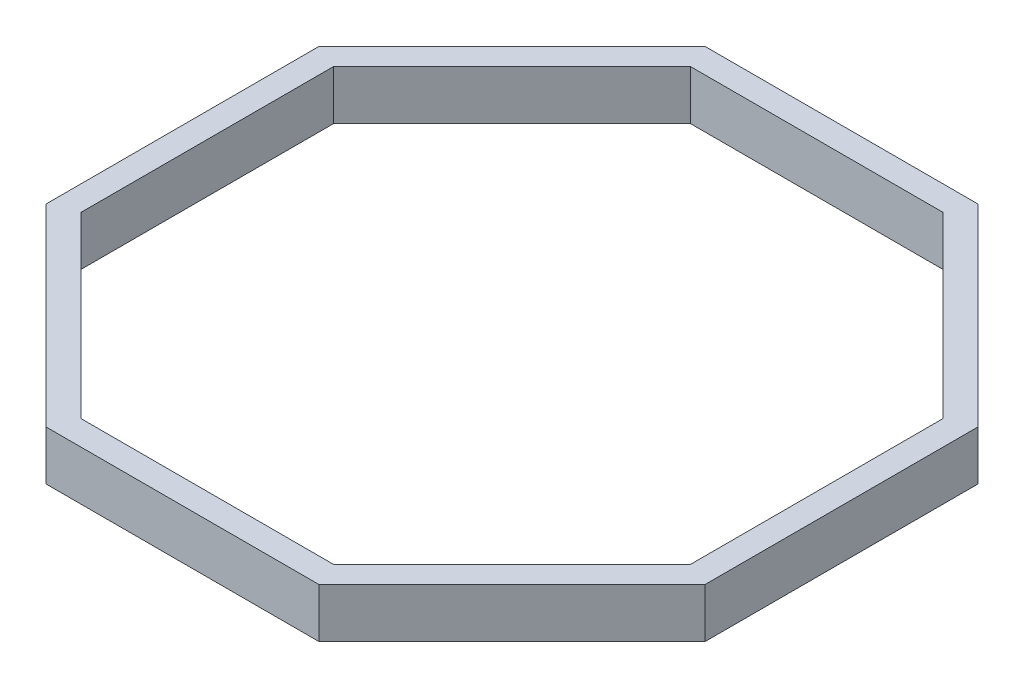
SolidWorks part; units mm, degrees
ref_plane "Plano frontal" through (0, 0, 0) normal (0, 0, 1) x (1, 0, 0)
ref_plane "Plano superior" through (0, 0, 0) normal (0, 1, 0) x (1, 0, 0)
ref_plane "Plano direito" through (0, 0, 0) normal (1, 0, 0) x (0, 0, -1)
sketch "Esboço2" plane through (0, 0, 0) normal (0, 1, 0) x (1, 0, 0)
  line L1 (200, 82.8427) -> (82.8427, 200)
  line L2 (82.8427, 200) -> (-82.8427, 200)
  line L3 (-82.8427, 200) -> (-200, 82.8427)
  line L4 (-200, 82.8427) -> (-200, -82.8427)
  line L5 (-200, -82.8427) -> (-82.8427, -200)
  line L6 (-82.8427, -200) -> (82.8427, -200)
  line L7 (82.8427, -200) -> (200, -82.8427)
  line L8 (200, -82.8427) -> (200, 82.8427)
  circle A0 centre (0, 0) radius 200 construction
extrude "Ressalto-extrusão1" add sketch "Esboço2" along normal blind 30
sketch "Esboço3" plane through (0, 30, 0) normal (0, 1, 0) x (1, 0, 0)
  line L1 (185, 76.6295) -> (76.6295, 185)
  line L2 (76.6295, 185) -> (-76.6295, 185)
  line L3 (-76.6295, 185) -> (-185, 76.6295)
  line L4 (-185, 76.6295) -> (-185, -76.6295)
  line L5 (-185, -76.6295) -> (-76.6295, -185)
  line L6 (-76.6295, -185) -> (76.6295, -185)
  line L7 (76.6295, -185) -> (185, -76.6295)
  line L8 (185, -76.6295) -> (185, 76.6295)
  circle A0 centre (0, 0) radius 185 construction
extrude "Corte-extrusão1" cut sketch "Esboço3" against normal blind 30
